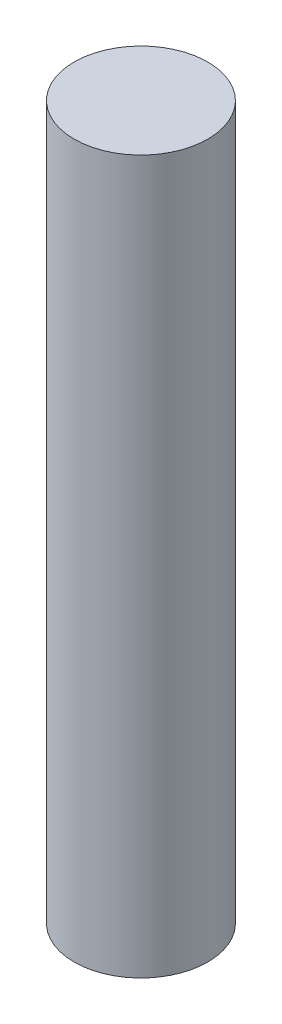
SolidWorks part; units mm, degrees
material "6061 Alloy"
ref_plane "Front Plane" through (0, 0, 0) normal (0, 0, 1) x (1, 0, 0)
ref_plane "Top Plane" through (0, 0, 0) normal (0, 1, 0) x (1, 0, 0)
ref_plane "Right Plane" through (0, 0, 0) normal (1, 0, 0) x (0, 0, -1)
sketch "Sketch1" plane through (0, 0, 0) normal (0, 1, 0) x (1, 0, 0)
  circle A0 centre (0, 0) radius 2.3813
  dimension "D1" = 4.7625
extrude "Boss-Extrude1" add sketch "Sketch1" along normal mid plane 25.4
